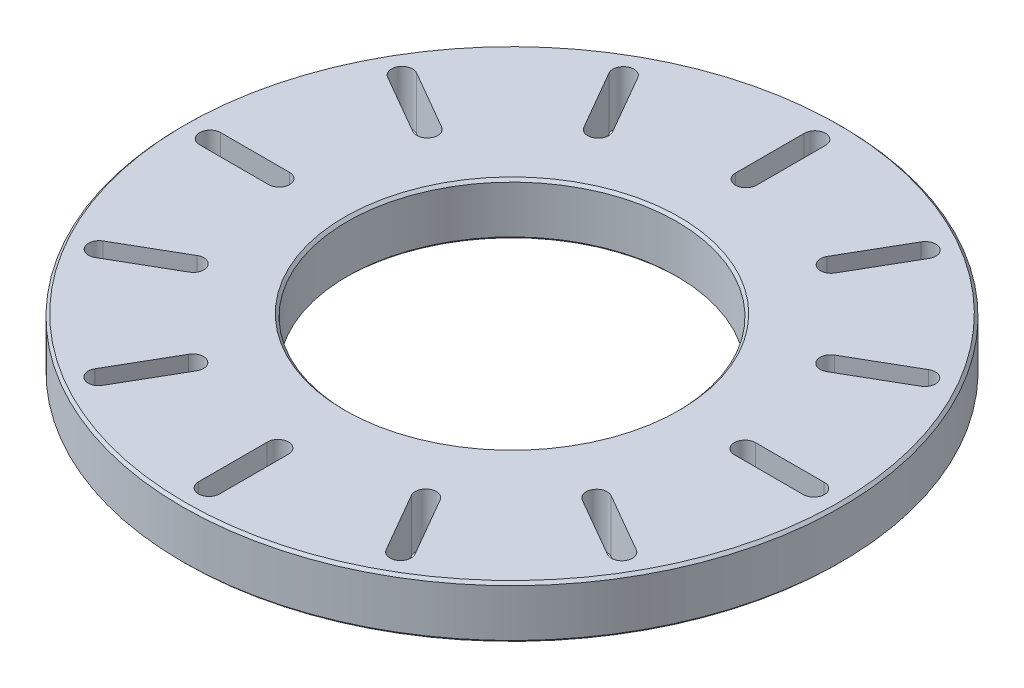
SolidWorks part; units mm, degrees
material "Plain Carbon Steel"
ref_plane "Front Plane" through (0, 0, 0) normal (0, 0, 1) x (1, 0, 0)
ref_plane "Top Plane" through (0, 0, 0) normal (0, 1, 0) x (1, 0, 0)
ref_plane "Right Plane" through (0, 0, 0) normal (1, 0, 0) x (0, 0, -1)
sketch "Sketch1" plane through (0, 0, 0) normal (0, 1, 0) x (1, 0, 0)
  line L0 (-0.7582, 17.7083) -> (-0.7582, 22.9528)
  line L1 (0.8419, 22.9403) -> (0.8415, 17.6884)
  line L2 (12.1992, 19.4459) -> (9.573, 14.8978)
  line L3 (8.1975, 15.715) -> (10.8197, 20.2568)
  line L4 (20.2878, 10.7411) -> (15.7393, 8.1154)
  line L5 (14.9567, 9.5108) -> (19.4986, 12.1331)
  line L6 (22.9403, -0.8419) -> (17.6884, -0.8415)
  line L7 (17.7083, 0.7582) -> (22.9528, 0.7582)
  line L8 (19.4459, -12.1992) -> (14.8978, -9.573)
  line L9 (15.715, -8.1975) -> (20.2568, -10.8197)
  line L10 (10.7411, -20.2878) -> (8.1154, -15.7393)
  line L11 (9.5108, -14.9567) -> (12.1331, -19.4986)
  line L12 (-0.8419, -22.9403) -> (-0.8415, -17.6884)
  line L13 (0.7582, -17.7083) -> (0.7582, -22.9528)
  line L14 (-12.1992, -19.4459) -> (-9.573, -14.8978)
  line L15 (-8.1975, -15.715) -> (-10.8197, -20.2568)
  line L16 (-20.2878, -10.7411) -> (-15.7393, -8.1154)
  line L17 (-14.9567, -9.5108) -> (-19.4986, -12.1331)
  line L18 (-22.9403, 0.8419) -> (-17.6884, 0.8415)
  line L19 (-17.7083, -0.7582) -> (-22.9528, -0.7582)
  line L20 (-19.4459, 12.1992) -> (-14.8978, 9.573)
  line L21 (-15.715, 8.1975) -> (-20.2568, 10.8197)
  line L22 (-10.7411, 20.2878) -> (-8.1154, 15.7393)
  line L23 (-9.5108, 14.9567) -> (-12.1331, 19.4986)
  arc A0 (9.5108, -14.9567) -> (8.1353, -15.7738) centre (8.818, -15.3567) ccw
  arc A1 (0.7582, -17.7083) -> (-0.8415, -17.7282) centre (-0.0418, -17.7083) ccw
  arc A2 (-8.1975, -15.715) -> (-9.5929, -14.9323) centre (-8.8903, -15.315) ccw
  arc A3 (-14.9567, -9.5108) -> (-15.7738, -8.1353) centre (-15.3567, -8.818) ccw
  arc A4 (-17.7083, -0.7582) -> (-17.7282, 0.8415) centre (-17.7083, 0.0418) ccw
  arc A5 (-15.715, 8.1975) -> (-14.9323, 9.5929) centre (-15.315, 8.8903) ccw
  arc A6 (-9.5108, 14.9567) -> (-8.1353, 15.7738) centre (-8.818, 15.3567) ccw
  arc A7 (-0.7582, 17.7083) -> (0.8415, 17.7282) centre (0.0418, 17.7083) ccw
  arc A8 (8.1975, 15.715) -> (9.5929, 14.9323) centre (8.8903, 15.315) ccw
  arc A9 (14.9567, 9.5108) -> (15.7738, 8.1353) centre (15.3567, 8.818) ccw
  arc A10 (17.7083, 0.7582) -> (17.7282, -0.8415) centre (17.7083, -0.0418) ccw
  arc A11 (15.715, -8.1975) -> (14.9323, -9.5929) centre (15.315, -8.8903) ccw
  circle A12 centre (0, 0) radius 25
  circle A13 centre (0, 0) radius 17.7084 construction
  circle A14 centre (0, 0) radius 22.9403 construction
  arc A15 (0.8417, 22.9249) -> (-0.7582, 22.9278) centre (0.0418, 22.9403) ccw
  arc A16 (12.1914, 19.4327) -> (10.8072, 20.2352) centre (11.5063, 19.846) ccw
  arc A17 (20.2744, 10.7335) -> (19.4769, 12.1206) centre (19.8878, 11.434) ccw
  arc A18 (22.9249, -0.8417) -> (22.9278, 0.7582) centre (22.9403, -0.0418) ccw
  arc A19 (19.4327, -12.1914) -> (20.2352, -10.8072) centre (19.846, -11.5063) ccw
  arc A20 (10.7335, -20.2744) -> (12.1206, -19.4769) centre (11.434, -19.8878) ccw
  arc A21 (-0.8417, -22.9249) -> (0.7582, -22.9278) centre (-0.0418, -22.9403) ccw
  arc A22 (-12.1914, -19.4327) -> (-10.8072, -20.2352) centre (-11.5063, -19.846) ccw
  arc A23 (-20.2744, -10.7335) -> (-19.4769, -12.1206) centre (-19.8878, -11.434) ccw
  arc A24 (-22.9249, 0.8417) -> (-22.9278, -0.7582) centre (-22.9403, 0.0418) ccw
  arc A25 (-19.4327, 12.1914) -> (-20.2352, 10.8072) centre (-19.846, 11.5063) ccw
  arc A26 (-10.7335, 20.2744) -> (-12.1206, 19.4769) centre (-11.434, 19.8878) ccw
  circle A27 centre (0, 0) radius 12.5
  point P27 (0, 0)
  point P115 (0, 0)
  dimension "D1" = 45.8807
  dimension "D3" = 25
  dimension "D4" = 0.8
  dimension "D2" = 12
extrude "Boss-Extrude1" add sketch "Sketch1" along normal blind 4 contours A12 A27 A26 L22 A6 L23 A25 L20 A5 L21 A24 L18 A4 L19 A23 L16 A3 L17 A22 L14 A2 L15 A21 L12 A1 L13 A20 L10 A0
chamfer "Chamfer1" distance 0.2 angle 45 4 edges at (0, 0, 12.5) (0, 4, 12.5) (0, 0, 25) (0, 4, 25)
